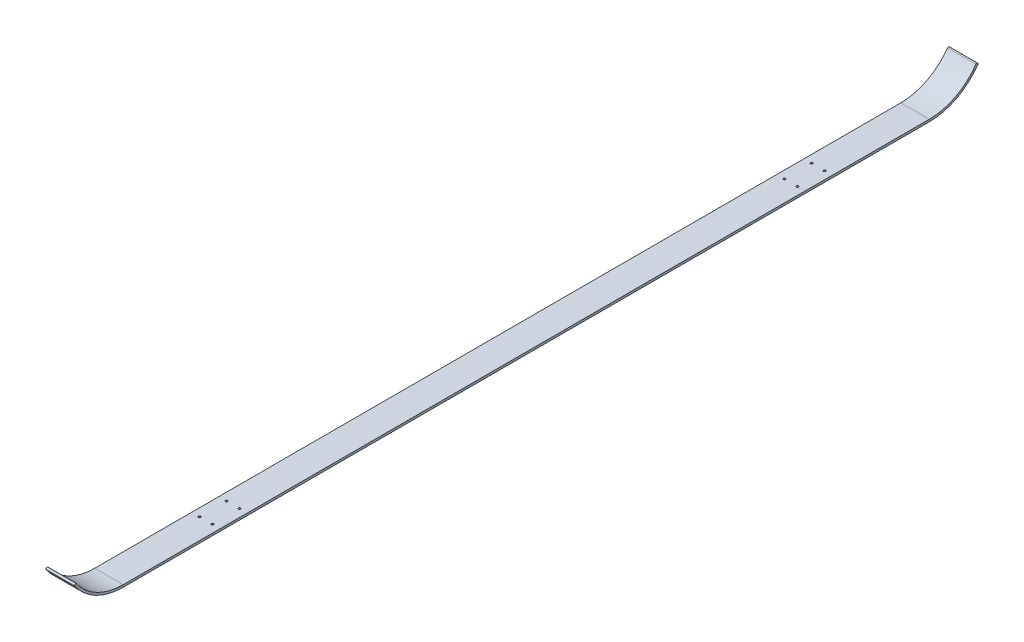
SolidWorks part; units mm, degrees
ref_plane "Front Plane" through (0, 0, 0) normal (0, 0, 1) x (1, 0, 0)
ref_plane "Top Plane" through (0, 0, 0) normal (0, 1, 0) x (1, 0, 0)
ref_plane "Right Plane" through (0, 0, 0) normal (1, 0, 0) x (0, 0, -1)
sketch "Sketch1" plane through (0, 0, 0) normal (0, 1, 0) x (1, 0, 0)
  line L0 (0, 1541.5) -> (0, -1541.5) construction
  line L1 (-75, -2024) -> (75, -2024)
  line L2 (-75, -2024) -> (-75, 2024)
  line L3 (-75, 2024) -> (75, 2024)
  line L4 (75, -2024) -> (75, 2024)
  line L5 (-75, -2024) -> (75, 2024) construction
  line L6 (-75, 2024) -> (75, -2024) construction
  line L7 (-75, 0) -> (75, 0) construction
  line L8 (-34.25, 1470.25) -> (34.25, 1470.25) construction
  line L9 (-34.25, 1470.25) -> (-34.25, 1612.75) construction
  line L10 (-34.25, 1612.75) -> (34.25, 1612.75) construction
  line L11 (34.25, 1470.25) -> (34.25, 1612.75) construction
  line L12 (-34.25, 1470.25) -> (34.25, 1612.75) construction
  line L13 (-34.25, 1612.75) -> (34.25, 1470.25) construction
  circle A0 centre (-34.25, 1470.25) radius 6
  circle A1 centre (34.25, 1470.25) radius 6
  circle A2 centre (-34.25, 1612.75) radius 6
  circle A3 centre (34.25, 1612.75) radius 6
  circle A4 centre (34.25, -1470.25) radius 6
  circle A5 centre (-34.25, -1470.25) radius 6
  circle A6 centre (34.25, -1612.75) radius 6
  circle A7 centre (-34.25, -1612.75) radius 6
  point P0 (0, 0)
  dimension "D6" = 12
  dimension "D1" = 150
  dimension "D2" = 4048
  dimension "D3" = 3083
  dimension "D4" = 142.5
  dimension "D5" = 68.5
extrude "Boss-Extrude1" add sketch "Sketch1" along normal blind 12
sketch "Sketch2" plane through (75, 0, 0) normal (1, 0, 0) x (0, 0, -1)
  line L0 (-2024, 0) -> (-2124, 0)
  line L1 (-2024, 0) -> (-2024, 12)
  line L2 (-2024, 12) -> (-2124, 12)
  line L3 (-2369.7456, 139.9271) -> (-2379.5754, 133.0442) construction
  line L4 (-2124, 0) -> (-2124, 312) construction
  line L5 (-2024, 6) -> (2024, 6) construction
  line L6 (2024, 12) -> (2024, 0) construction
  line L7 (0, 0) -> (0, 12) construction
  line L8 (-2024, 12) -> (2024, 12) construction
  line L9 (2024, 12) -> (2124, 12)
  line L10 (2024, 0) -> (2024, 12)
  line L11 (2024, 0) -> (2124, 0)
  arc A0 (-2369.7456, 139.9271) -> (-2124, 12) centre (-2124, 312) ccw
  arc A1 (-2379.5754, 133.0442) -> (-2124, 0) centre (-2124, 312) ccw
  arc A2 (-2369.7456, 139.9271) -> (-2379.5754, 133.0442) centre (-2374.6605, 136.4856) ccw
  arc A3 (2369.7456, 139.9271) -> (2124, 12) centre (2124, 312) cw
  arc A4 (2379.5754, 133.0442) -> (2124, 0) centre (2124, 312) cw
  arc A5 (2369.7456, 139.9271) -> (2379.5754, 133.0442) centre (2374.6605, 136.4856) cw
  dimension "D3" = 300
  dimension "D1" = 100
  dimension "D2" = 55
extrude "Boss-Extrude2" add sketch "Sketch2" along direction (1, 0, 0) on the side against the normal up to surface (150 mm away)
equation "\"mbtOD\" = 500"
equation "\"mbtT\" = 6"
equation "\"mbtL\" = 3000"
equation "\"mbtFlangeOD\" = 650"
equation "\"mbtFlangeT\" = 12"
equation "\"mbtFlangeBoltCircleDia\" = 650"
equation "\"mbtFlangeHoleDia\" = 12"
equation "\"mbtOringSize\" = 10 "
equation "\"mbtOringDia\" = 620"
equation "\"mbtWidth\" = 2250"
equation "\"skiWidth\" = 1250"
equation "\"D2@Sketch1\"=\"mbtL\"+4*\"mbtFlangeT\"+2*\"mbtCapL\""
equation "\"mbtCapL\" = 500"
equation "\"D3@Sketch1\"=\"mbtL\"+4*\"mbtFlangeT\"+35mm"
